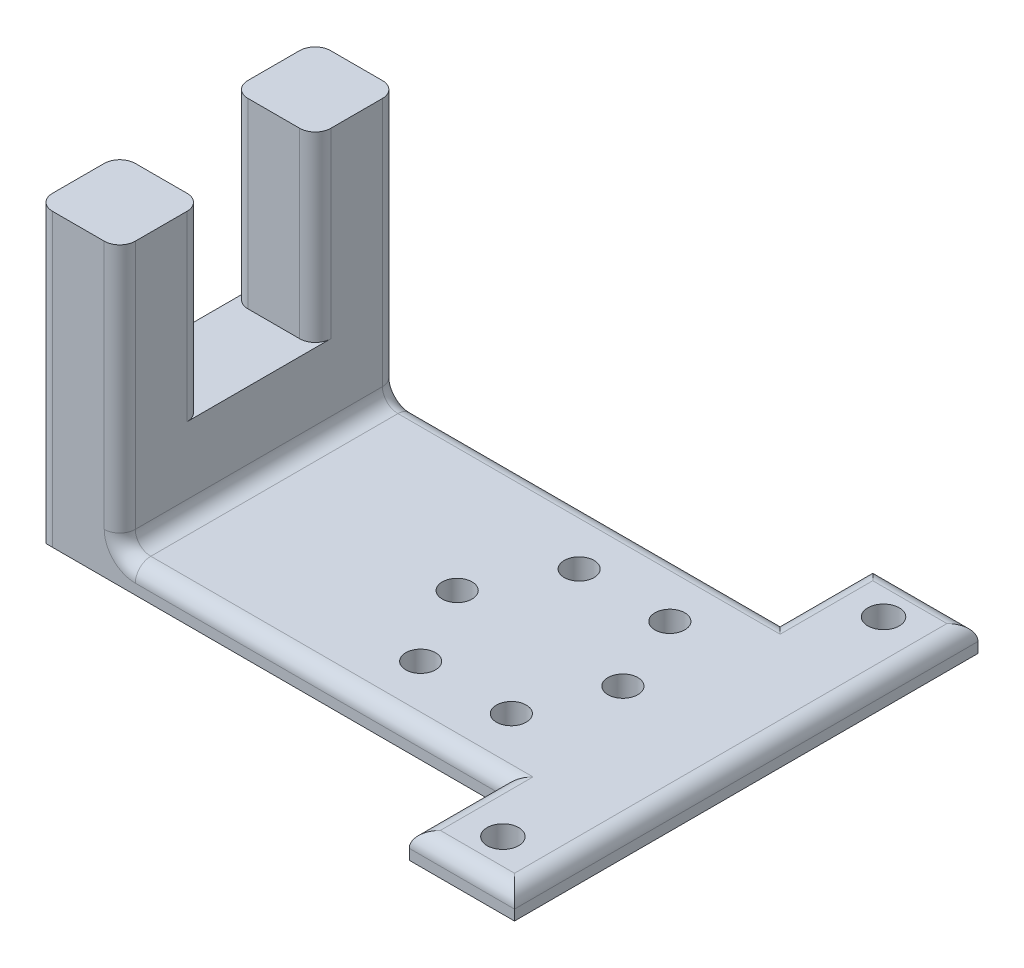
SolidWorks part; units mm, degrees
material "PF"
ref_plane "Front Plane" through (0, 0, 0) normal (0, 0, 1) x (1, 0, 0)
ref_plane "Top Plane" through (0, 0, 0) normal (0, 1, 0) x (1, 0, 0)
ref_plane "Right Plane" through (0, 0, 0) normal (1, 0, 0) x (0, 0, -1)
sketch "Sketch1" plane through (0, 0, 0) normal (0, 1, 0) x (1, 0, 0)
  line L0 (34.4102, -8.1112) -> (81.0734, -8.1112) construction
  line L1 (34.4102, 13.2088) -> (-36.8698, 13.2088)
  line L2 (34.4102, 13.2088) -> (34.4102, -29.4312)
  line L3 (34.4102, -29.4312) -> (-36.8698, -29.4312)
  line L4 (-36.8698, 13.2088) -> (-36.8698, -29.4312)
  dimension "D1" = 21.32
  dimension "D2" = 71.28
  dimension "D3" = 21.32
extrude "Boss-Extrude1" add sketch "Sketch1" along normal blind 6.35
sketch "Sketch3" plane through (0, 6.35, 0) normal (0, 1, 0) x (1, 0, 0)
  line L0 (34.4102, 13.2088) -> (-36.8698, 13.2088) construction
  line L1 (-24.1698, -29.4312) -> (-36.8698, -29.4312)
  line L2 (-24.1698, -29.4312) -> (-24.1698, 13.2088)
  line L3 (-24.1698, 13.2088) -> (-36.8698, 13.2088)
  line L4 (-36.8698, -29.4312) -> (-36.8698, 13.2088)
  line L6 (34.4102, -29.4312) -> (34.4102, 13.2088) construction
  dimension "D1" = 58.58
  dimension "D2" = 42.64
extrude "Boss-Extrude3" add sketch "Sketch3" along normal blind 12.7
sketch "Sketch4" plane through (0, 19.05, 0) normal (0, 1, 0) x (1, 0, 0)
  line L0 (-24.1698, -29.4312) -> (-24.1698, 13.2088) construction
  line L1 (-36.8698, -29.4312) -> (-24.1698, -29.4312)
  line L2 (-36.8698, -29.4312) -> (-36.8698, -16.7312)
  line L3 (-36.8698, -16.7312) -> (-24.1698, -16.7312)
  line L4 (-24.1698, -29.4312) -> (-24.1698, -16.7312)
  line L5 (-36.8698, -29.4312) -> (-24.1698, -29.4312) construction
  line L6 (-36.8698, 12.2088) -> (-24.1698, 12.2088)
  line L7 (-36.8698, 12.2088) -> (-36.8698, -0.4912)
  line L8 (-36.8698, -0.4912) -> (-24.1698, -0.4912)
  line L9 (-24.1698, 12.2088) -> (-24.1698, -0.4912)
  dimension "D1" = 12.7
  dimension "D2" = 12.7
extrude "Boss-Extrude4" add sketch "Sketch4" along normal blind 27.94 contours L2 L1 L4 L3
sketch "Sketch6" plane through (0, 19.05, 0) normal (0, 1, 0) x (1, 0, 0)
  line L0 (-24.1698, -16.7312) -> (-24.1698, 13.2088) construction
  line L1 (-36.8698, 13.2088) -> (-24.1698, 13.2088)
  line L2 (-36.8698, 13.2088) -> (-36.8698, 0.5327)
  line L3 (-36.8698, 0.5327) -> (-24.1698, 0.5327)
  line L4 (-24.1698, 13.2088) -> (-24.1698, 0.5327)
  line L5 (-24.1698, 13.2088) -> (-36.8698, 13.2088) construction
extrude "Boss-Extrude5" add sketch "Sketch6" along normal blind 27.94
sketch "Sketch7" plane through (0, 6.35, 0) normal (0, 1, 0) x (1, 0, 0)
  line L2 (-24.1698, -29.4312) -> (-24.1698, 13.2088) construction
  circle A0 centre (6.2302, -8.1112) radius 2.286
  circle A1 centre (31.6302, -8.1112) radius 2.286
  circle A2 centre (12.7302, 4.0888) radius 2.285
  circle A3 centre (12.8302, -20.3112) radius 2.285
  circle A4 centre (26.6302, 4.0888) radius 2.285
  circle A5 centre (26.7302, -20.3112) radius 2.285
  dimension "D4" = 4.572
  dimension "D2" = 4.57
  dimension "D7" = 4.57
  dimension "D10" = 4.57
  dimension "D11" = 4.57
  dimension "D1" = 30.4
  dimension "D5" = 6.5
  dimension "D6" = 12.2
  dimension "D8" = 12.2
  dimension "D9" = 13.9
  dimension "D12" = 13.9
  dimension "D3" = 2
extrude "Cut-Extrude1" cut sketch "Sketch7" against normal through all
sketch "Sketch10" plane through (0, 6.35, 0) normal (0, 1, 0) x (1, 0, 0)
  line L0 (31.6302, -8.1112) -> (42.4747, -8.1112) construction
  line L1 (34.4102, -29.4312) -> (34.4102, 13.2088) construction
  line L3 (50.5392, 27.4118) -> (34.4102, 27.4118)
  line L4 (50.5392, 27.4118) -> (50.5392, -43.6342)
  line L5 (50.5392, -43.6342) -> (34.4102, -43.6342)
  line L6 (34.4102, 27.4118) -> (34.4102, -43.6342)
  line L7 (50.5392, 27.4118) -> (34.4102, -43.6342) construction
  line L8 (50.5392, -43.6342) -> (34.4102, 27.4118) construction
  dimension "D1" = 8.0645
  dimension "D2" = 16.129
  dimension "D3" = 71.046
extrude "Boss-Extrude6" add sketch "Sketch10" against normal blind 6.35
sketch "Sketch11" plane through (0, 6.35, 0) normal (0, 1, 0) x (1, 0, 0)
  line L0 (50.5392, -43.6342) -> (50.5392, 27.4118) construction
  line L1 (50.5392, 27.4118) -> (34.4102, 27.4118) construction
  line L2 (34.4102, -43.6342) -> (50.5392, -43.6342) construction
  circle A0 centre (42.4112, 21.0618) radius 2.413
  circle A1 centre (42.4112, -37.2842) radius 2.413
  dimension "D3" = 4.826
  dimension "D6" = 4.826
  dimension "D1" = 8.128
  dimension "D2" = 6.35
  dimension "D4" = 8.128
  dimension "D5" = 6.35
extrude "Cut-Extrude2" cut sketch "Sketch11" against normal blind 6.35
chamfer "Chamfer1" distance 2.38 angle 45 8 edges at (-36.8698, 0, 8.1112) (-1.2298, 0, -13.2088) (34.4102, 0, -20.3103) (42.4747, 0, -27.4118) (50.5392, 0, 8.1112) (42.4747, 0, 43.6342) (34.4102, 0, 36.5327) (-1.2298, 0, 29.4312)
fillet "Fillet1" radius 2.38 16 edges at (-24.1698, 26.67, -13.2088) (-36.8698, 33.02, -0.5327) (-36.8698, 24.685, -13.2088) (-24.1698, 6.35, 8.1112) (-24.1698, 33.02, -0.5327) (-36.8698, 33.02, 16.7312) (-24.1698, 33.02, 16.7312) (-36.8698, 24.685, 29.4312) (-24.1698, 26.67, 29.4312) (5.1202, 6.35, -13.2088) (34.4102, 6.35, -20.3103) (42.4747, 6.35, -27.4118) (50.5392, 6.35, 8.1112) (42.4747, 6.35, 43.6342) (34.4102, 6.35, 36.5327) (5.1202, 6.35, 29.4312)
